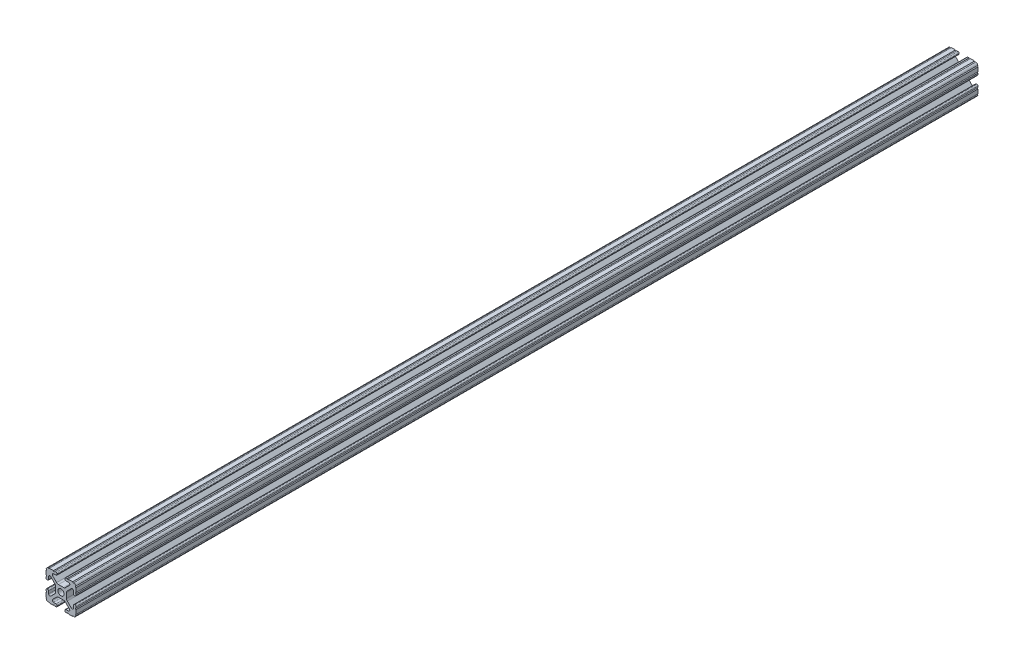
SolidWorks part; units mm, degrees
ref_plane "Front Plane" through (0, 0, 0) normal (0, 0, 1) x (1, 0, 0)
ref_plane "Top Plane" through (0, 0, 0) normal (0, 1, 0) x (1, 0, 0)
ref_plane "Right Plane" through (0, 0, 0) normal (1, 0, 0) x (0, 0, -1)
sketch "Sketch2" plane through (0, 0, 0) normal (0, 0, 1) x (1, 0, 0)
  line L0 (0, 12.7) -> (0, -12.7) construction
  line L1 (-12.7, 0) -> (12.7, 0) construction
  line L2 (3.2512, -12.7) -> (12.7, -12.7)
  line L3 (12.7, -12.7) -> (12.7, -3.2512)
  line L4 (3.2512, -12.7) -> (3.2512, -10.4902)
  line L5 (3.2512, -10.4902) -> (8.9276, -10.4902)
  line L6 (8.9276, -10.4902) -> (3.0856, -4.6482)
  line L7 (0, 0) -> (12.7, -12.7) construction
  line L8 (12.7, -3.2512) -> (10.4902, -3.2512)
  line L9 (10.4902, -3.2512) -> (10.4902, -8.9276)
  line L10 (10.4902, -8.9276) -> (4.6482, -3.0856)
  circle A0 centre (0, 0) radius 2.6035
  arc A1 (6.3485, -10.4902) -> (7.1039, -8.6665) centre (6.3485, -9.4219) ccw construction
  point P8 (0, -4.6482)
  dimension "Center Hole Diameter" = 5.207
  dimension "Rail Height" = 25.4
  dimension "Rail Width" = 25.4
  dimension "T-Slot Width" = 6.5024
  dimension "Slot Inner Width" = 14.8336
  dimension "Thickness" = 2.2098
  dimension "Slot Depth" = 5.842
  dimension "D1" = 2.2098
sketch "Sketch3" plane through (0, 0, 0) normal (1, 0, 0) x (0, 0, -1)
  line L0 (-381, -12.7) -> (381, -12.7) construction
  line L1 (-355.6, 0) -> (355.6, 0) construction
  dimension "Length" = 762
  dimension "D1" = 25.4
sketch "Sketch4" plane through (0, 0, 0) normal (0, 0, 1) x (1, 0, 0)
  line L0 (4.1904, -12.7) -> (10.1173, -12.7)
  line L1 (3.2512, -12.7) -> (12.7, -12.7) construction
  line L2 (3.2512, -12.7) -> (3.2512, -10.4902) construction
  line L3 (3.2512, -10.4902) -> (8.9276, -10.4902) construction
  line L4 (3.2512, -11.4294) -> (3.2512, -11.7608)
  line L5 (4.1904, -10.4902) -> (6.3485, -10.4902)
  line L6 (0, -4.6482) -> (2.164, -4.6482)
  line L7 (8.9276, -10.4902) -> (3.0856, -4.6482) construction
  line L8 (3.7373, -5.2999) -> (7.1039, -8.6665)
  line L9 (12.7, -12.7) -> (12.7, -3.2512) construction
  line L10 (10.4902, -8.9276) -> (4.6482, -3.0856) construction
  line L11 (10.4902, -3.2512) -> (10.4902, -8.9276) construction
  line L12 (10.4902, -6.3485) -> (10.4902, -4.1904)
  line L13 (12.7, -3.2512) -> (10.4902, -3.2512) construction
  line L14 (11.4294, -3.2512) -> (11.7608, -3.2512)
  line L15 (12.7, -4.1904) -> (12.7, -10.1173)
  line L16 (8.6665, -7.1039) -> (5.2999, -3.7373)
  line L17 (4.6482, 0) -> (4.6482, -2.164)
  line L18 (-12.7, 0) -> (12.7, 0) construction
  line L19 (0, -4.6482) -> (0, -2.6035)
  line L20 (0, 12.7) -> (0, -12.7) construction
  line L21 (4.6482, 0) -> (2.6035, 0)
  arc A0 (3.2512, -11.7608) -> (4.1904, -12.7) centre (4.1904, -11.7608) ccw
  arc A2 (3.2512, -11.4294) -> (4.1904, -10.4902) centre (4.1904, -11.4294) cw
  arc A3 (6.3485, -10.4902) -> (7.1039, -8.6665) centre (6.3485, -9.4219) ccw
  arc A4 (2.164, -4.6482) -> (3.7373, -5.2999) centre (2.164, -6.8732) cw
  arc A5 (10.1173, -12.7) -> (12.7, -10.1173) centre (10.1173, -10.1173) ccw
  arc A6 (8.6665, -7.1039) -> (10.4902, -6.3485) centre (9.4219, -6.3485) ccw
  arc A7 (10.4902, -4.1904) -> (11.4294, -3.2512) centre (11.4294, -4.1904) cw
  arc A8 (11.7608, -3.2512) -> (12.7, -4.1904) centre (11.7608, -4.1904) cw
  arc A9 (5.2999, -3.7373) -> (4.6482, -2.164) centre (6.8732, -2.164) cw
  circle A10 centre (0, 0) radius 2.6035 construction
  arc A11 (0, -2.6035) -> (2.6035, 0) centre (0, 0) ccw
  dimension "D1" = 2.5827
  dimension "D2" = 2.225
  dimension "D3" = 0.9392
extrude "Boss-Extrude1" add sketch "Sketch4" along normal mid plane 762
sketch "Sketch5" plane through (0, 0, 0) normal (0, 0, 1) x (1, 0, 0)
  line L0 (3.2512, -12.7) -> (12.7, -12.7) construction
  line L1 (4.1904, -10.4902) -> (6.3485, -10.4902) construction
  line L3 (0, 0) -> (12.7, -12.7) construction
  line L4 (6.3485, -10.4902) -> (6.3485, -12.7) construction
  line L5 (8.9276, -10.4902) -> (3.0856, -4.6482) construction
  circle A0 centre (10.3562, -12.7) radius 0.5524
  circle A1 centre (5.796, -12.7) radius 0.5524
  circle A2 centre (12.7, -10.3562) radius 0.5524
  circle A3 centre (12.7, -5.796) radius 0.5524
  point P10 (5.2694, -10.4902)
  point P12 (9.4219, -6.3485)
  dimension "D1" = 1.1049
extrude "Cut-Extrude1" cut sketch "Sketch5" against normal through all both and the other way through all
mirror "Mirror1" about plane through (0, 0, 0) normal (1, 0, 0) of bodies 137 134
mirror "Mirror2" about plane through (0, 0, 0) normal (0, 1, 0) of bodies 135
equation "\"D1@Boss-Extrude1\"=\"Length@Sketch3\""
equation "\"D1@Sketch2\"=\"Thickness@Sketch2\""
equation "\"D2@Sketch4\"=\"Slot Inner Width@Sketch2\"*0.15"
equation "\"D1@Sketch4\"=\"D3@Sketch4\"*2.75"
equation "\"D3@Sketch4\"=\"Thickness@Sketch2\"*0.425"
equation "\"D1@Sketch5\"=\"Thickness@Sketch2\"*0.5"
